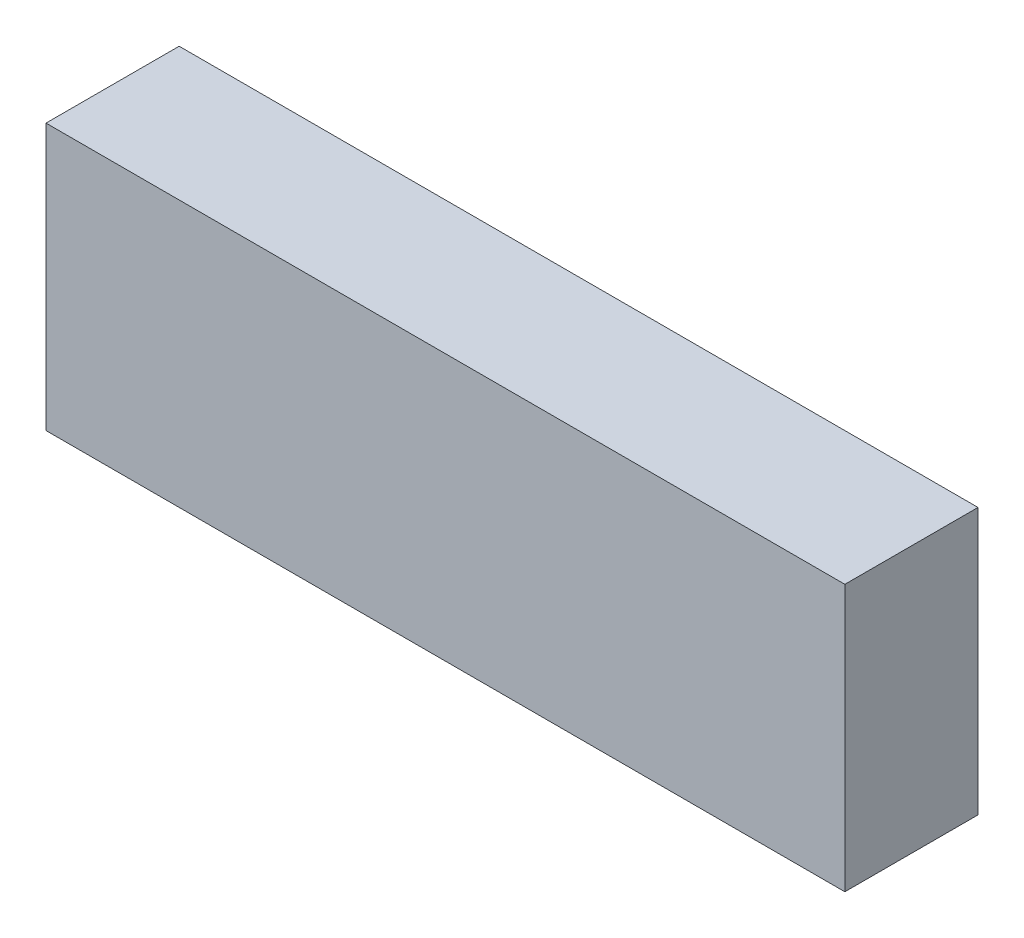
SolidWorks part; units mm, degrees
material "Copper"
ref_plane "Front Plane" through (0, 0, 0) normal (0, 0, 1) x (1, 0, 0)
ref_plane "Top Plane" through (0, 0, 0) normal (0, 1, 0) x (1, 0, 0)
ref_plane "Right Plane" through (0, 0, 0) normal (1, 0, 0) x (0, 0, -1)
sketch "Sketch1" plane through (0, 0, 0) normal (0, 0, 1) x (1, 0, 0)
  line L1 (-76.2, -25.4) -> (76.2, -25.4)
  line L2 (-76.2, -25.4) -> (-76.2, 25.4)
  line L3 (-76.2, 25.4) -> (76.2, 25.4)
  line L4 (76.2, -25.4) -> (76.2, 25.4)
  line L5 (-76.2, -25.4) -> (76.2, 25.4) construction
  line L6 (-76.2, 25.4) -> (76.2, -25.4) construction
  point P0 (0, 0)
  dimension "D1" = 152.4
  dimension "D2" = 50.8
extrude "Boss-Extrude1" add sketch "Sketch1" along normal blind 25.4
